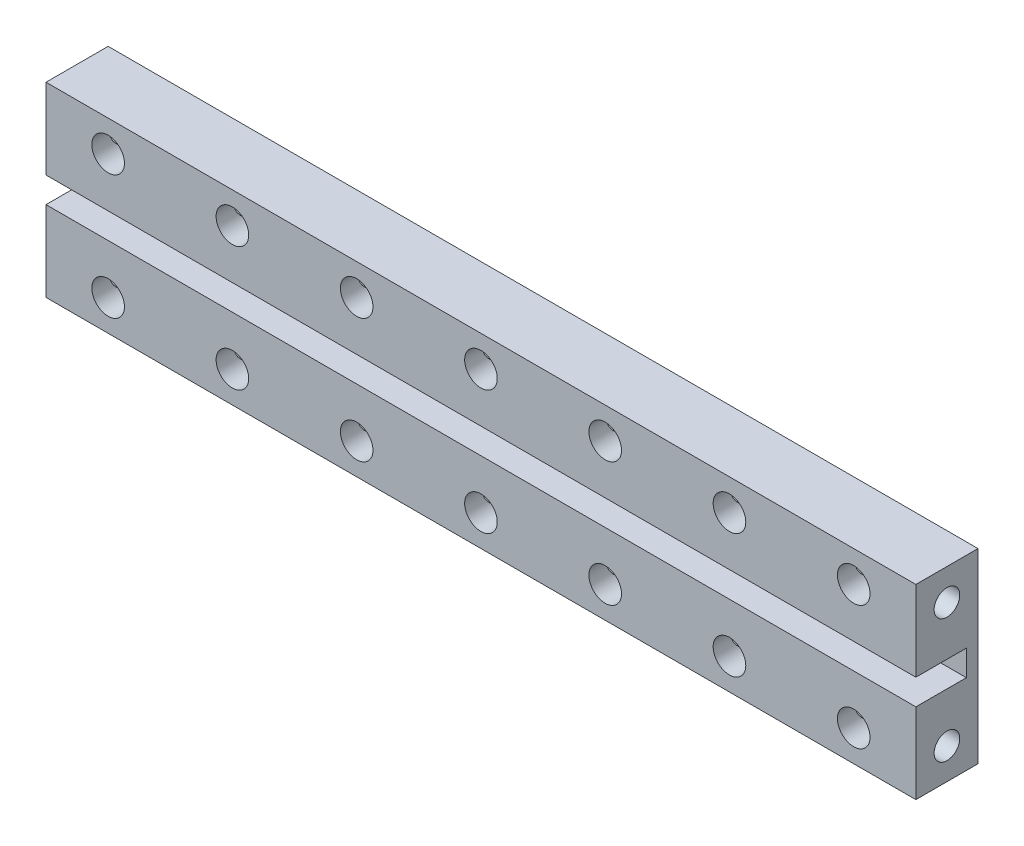
SolidWorks part; units mm, degrees
ref_plane "Front Plane" through (0, 0, 0) normal (0, 0, 1) x (1, 0, 0)
ref_plane "Top Plane" through (0, 0, 0) normal (0, 1, 0) x (1, 0, 0)
ref_plane "Right Plane" through (0, 0, 0) normal (1, 0, 0) x (0, 0, -1)
sketch "Sketch2" plane through (0, 0, 0) normal (1, 0, 0) x (0, 0, -1)
  line L0 (0, 12) -> (-8, 12)
  line L1 (0, 12) -> (0, -12)
  line L5 (-8, 12) -> (-8, 1.65)
  line L6 (-8, 1.65) -> (-1.5, 1.65)
  line L7 (-1.5, 1.65) -> (-1.5, -1.65)
  line L8 (-1.5, -1.65) -> (-8, -1.65)
  line L9 (-8, -12) -> (0, -12)
  line L10 (-8, -12) -> (-8, -1.65)
extrude "Boss-Extrude1" add sketch "Sketch2" along normal blind 112
hole_wizard "Tap Drill for M4x0.7 Tap1" positions "Sketch4" profile "Sketch3" hole size "M4x0.7" standard "ANSI Metric"
sketch "Sketch4" plane through (0, 0, 0) normal (-1, 0, 0) x (0, 0, 1)
  line L0 (0, -12) -> (0, 12) construction
  point P0 (4, 8)
  point P2 (4, -8)
  dimension "D1" = 4
  dimension "D2" = 8
  dimension "D3" = 16
sketch "Sketch3" plane through (0, 8, 4) normal (0, 1, 0) x (0, 0, 1)
  line L0 (0, 0) -> (0, 112.9904)
  line L1 (0, 112.9904) -> (1.65, 111.999)
  line L2 (1.65, 111.999) -> (1.65, 0)
  line L5 (1.65, 0) -> (0, 0)
  line L10 (0, 112.9904) -> (-1.65, 111.999) construction
  line L11 (0, -6.35) -> (0, 107.95) construction
  dimension "Hole Dia." = 3.3
  dimension "Hole Depth" = 111.999
  dimension "Drill Angle" = 118
hole_wizard "Ø4.2 (4.2) Diameter Hole2" positions "Sketch6" profile "Sketch5" hole size "Ø4.2" standard "ANSI Metric"
sketch "Sketch6" plane through (0, 0, 8) normal (0, 0, 1) x (1, 0, 0)
  line L0 (0, 12) -> (0, 1.65) construction
  line L1 (112, 12) -> (0, 12) construction
  point P0 (8, 8)
  point P2 (8, -8)
  dimension "D1" = 8
  dimension "D2" = 4
  dimension "D3" = 16
sketch "Sketch5" plane through (8, 8, 8) normal (1, 0, 0) x (0, -1, 0)
  line L0 (0, 0) -> (0, 9.2608)
  line L1 (0, 9.2608) -> (2.1, 7.999)
  line L2 (2.1, 7.999) -> (2.1, 0)
  line L5 (2.1, 0) -> (0, 0)
  line L10 (0, 9.2608) -> (-2.1, 7.999) construction
  line L11 (0, -6.35) -> (0, 107.95) construction
  dimension "Hole Dia." = 4.2
  dimension "Hole Depth" = 7.999
  dimension "Drill Angle" = 118
pattern_linear "LPattern1" count 7 spacing 16 along (1, 0, 0) of "Ø4.2 (4.2) Diameter Hole2"
